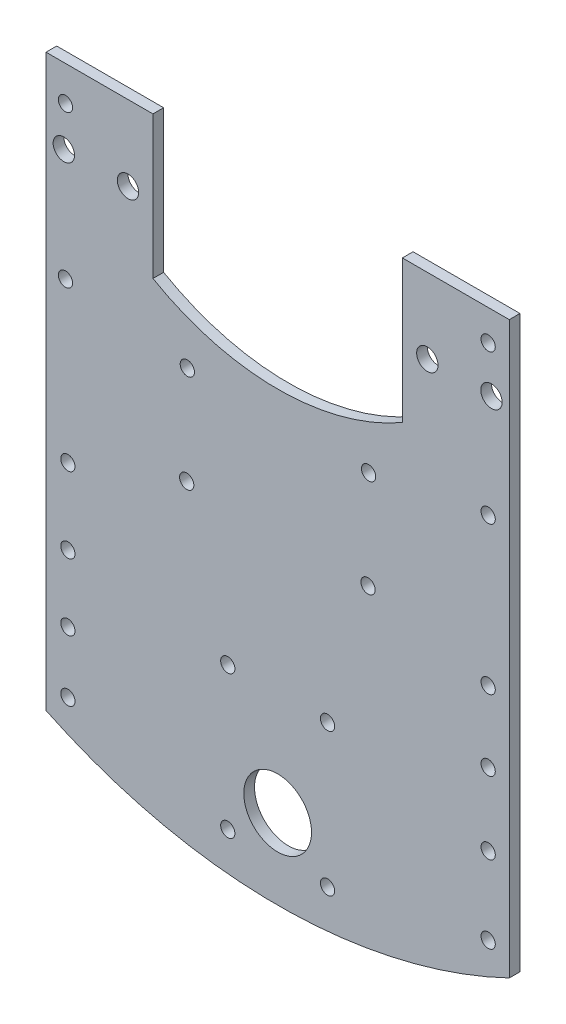
SolidWorks part; units mm, degrees
material "6063-O"
ref_plane "Front Plane" through (0, 0, 0) normal (0, 0, 1) x (1, 0, 0)
ref_plane "Top Plane" through (0, 0, 0) normal (0, 1, 0) x (1, 0, 0)
ref_plane "Right Plane" through (0, 0, 0) normal (1, 0, 0) x (0, 0, -1)
sketch "Sketch1" plane through (0, 0, 0) normal (0, 0, 1) x (1, 0, 0)
  line L1 (-34.1797, 1.6565) -> (-34.1797, 41.6565)
  line L2 (-34.1797, 41.6565) -> (-64.1797, 41.6565)
  line L3 (-64.1797, 41.6565) -> (-64.1797, -118.3435)
  line L5 (65.8203, -118.3435) -> (65.8203, 41.6565)
  line L6 (65.8203, 41.6565) -> (35.8203, 41.6565)
  line L7 (35.8203, 41.6565) -> (35.8203, 1.6565)
  arc A0 (-34.1797, 1.6565) -> (35.8203, 1.6565) centre (0.8203, 62.2783) ccw
  arc A1 (-64.1797, -118.3435) -> (65.8203, -118.3435) centre (0.8203, 16.8416) ccw
  circle A2 centre (60.8203, 20.5545) radius 3
  circle A3 centre (42.8203, 20.5545) radius 3
  circle A4 centre (-59.1797, 20.5545) radius 3
  circle A5 centre (-41.1797, 20.5545) radius 3
  point P4 (0, 0)
  dimension "D7" = 70
  dimension "D8" = 150
  dimension "D9" = 6
  dimension "D10" = 6
  dimension "D1" = 130
  dimension "D2" = 30
  dimension "D3" = 30
  dimension "D4" = 40
  dimension "D5" = 40
  dimension "D6" = 160
  dimension "D12" = 18
  dimension "D13" = 84
  dimension "D14" = 18
  dimension "D15" = 160
  dimension "D16" = 21.1021
  dimension "D17" = 41.1797
extrude "Boss-Extrude2" add sketch "Sketch1" along normal blind 3
sketch "Sketch4" plane through (0, 0, 3) normal (0, 0, 1) x (1, 0, 0)
  line L0 (-34.1797, 1.6565) -> (65.8203, -118.3435) construction
  line L2 (35.8203, 1.6565) -> (-64.1797, -118.3435) construction
  line L4 (0.8203, -7.7217) -> (0.8203, -164.587) construction
  circle A4 centre (0.8203, -110.7217) radius 9.5
  arc A5 (-34.1797, 1.6565) -> (35.8203, 1.6565) centre (0.8203, 62.2783) ccw construction
  point P0 (0.8203, -110.7217)
  point P17 (0.8203, -68.979)
  dimension "D4" = 19
  dimension "D1" = 103
extrude "Cut-Extrude2" cut sketch "Sketch4" against normal blind 10
sketch "Sketch5" plane through (0, 0, 0) normal (0, 0, -1) x (-1, 0, 0)
  circle A4 centre (-14.8203, -121.7217) radius 2 construction
  circle A5 centre (-14.8203, -121.7217) radius 2
  circle A6 centre (-14.8203, -81.7217) radius 2 construction
  circle A7 centre (13.1797, -81.7217) radius 2 construction
  circle A8 centre (13.1797, -121.7217) radius 2 construction
  circle A9 centre (-14.8203, -81.7217) radius 2
  circle A10 centre (13.1797, -81.7217) radius 2
  circle A11 centre (13.1797, -121.7217) radius 2
extrude "Cut-Extrude3" cut sketch "Sketch5" against normal up to surface (3 mm away) up to face at (10.3203, -110.7217, 3)
sketch "Sketch6" plane through (0, 0, 0) normal (0, 0, -1) x (-1, 0, 0)
  line L0 (-35.8203, 41.6565) -> (-35.8203, 1.6565) construction
  line L1 (34.1797, 41.6565) -> (64.1797, 41.6565) construction
  circle A0 centre (-26.1701, -42.8703) radius 2
  circle A1 centre (-26.3397, -15.2903) radius 2
  circle A2 centre (24.5295, -15.2903) radius 2
  circle A3 centre (24.6991, -42.8703) radius 2
  dimension "D1" = 4
  dimension "D2" = 4
  dimension "D3" = 4
  dimension "D4" = 4
  dimension "D5" = 9.4806
  dimension "D6" = 9.6502
  dimension "D7" = 60.3498
  dimension "D8" = 60.5194
  dimension "D9" = 56.9468
  dimension "D10" = 84.5268
extrude "Cut-Extrude4" cut sketch "Sketch6" against normal up to surface (3 mm away) up to face at (-11.1797, -121.7217, 3)
sketch "Sketch7" plane through (0, 0, 3) normal (0, 0, 1) x (1, 0, 0)
  circle A0 centre (-58.0508, -112.0762) radius 2
  circle A1 centre (-58.0508, -94.9619) radius 2
  circle A2 centre (-58.0508, -76.2503) radius 2
  circle A3 centre (-58.0508, -55.0286) radius 2
  circle A4 centre (-58.7353, -10.7596) radius 2
  circle A5 centre (-58.7353, 31.9013) radius 2
  circle A6 centre (59.8927, -112.1154) radius 2
  circle A7 centre (59.8927, -90.4056) radius 2
  circle A8 centre (59.8927, -70.122) radius 2
  circle A9 centre (59.8927, -50.2558) radius 2
  circle A10 centre (59.8927, -8.8259) radius 2
  circle A11 centre (59.8927, 33.0331) radius 2
  circle A12 centre (14.8203, -81.7217) radius 2 construction
  dimension "D1" = 4
  dimension "D2" = 45.0724
  dimension "D3" = 72.8711
  dimension "D4" = 73.5557
  dimension "D5" = 5.4714
  dimension "D6" = 11.5997
  dimension "D7" = 26.6931
  dimension "D8" = 31.4658
  dimension "D9" = 70.962
  dimension "D10" = 72.8958
  dimension "D11" = 113.623
  dimension "D12" = 114.7548
  dimension "D13" = 8.6839
  dimension "D14" = 13.2402
  dimension "D15" = 30.3545
  dimension "D16" = 30.3937
extrude "Cut-Extrude5" cut sketch "Sketch7" against normal blind 10
